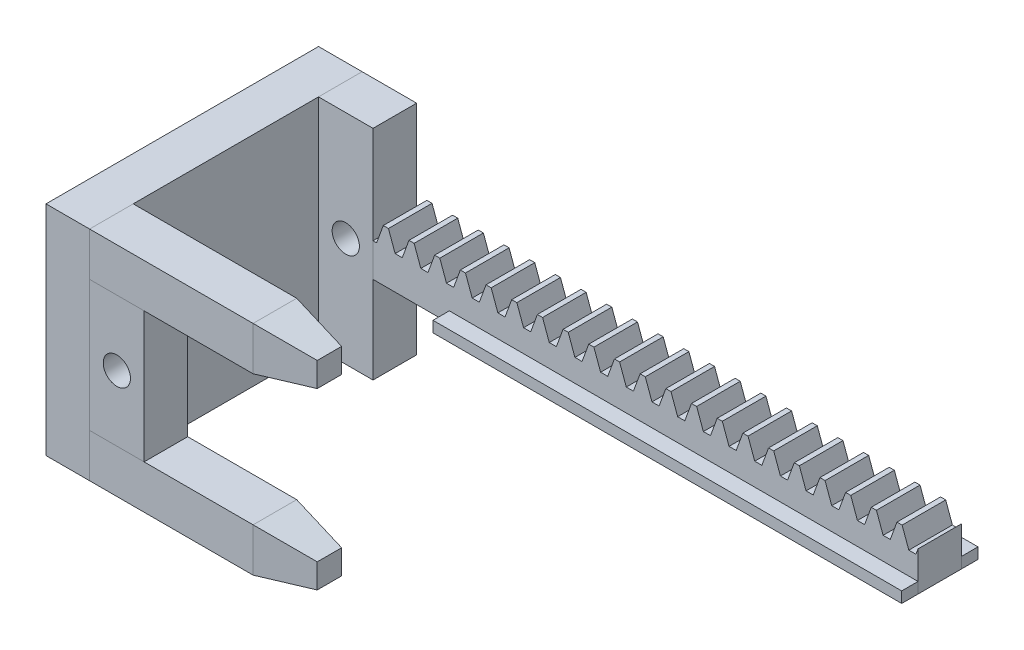
SolidWorks part; units mm, degrees
other "CutExtrude1"
other "BodyMoveCopy12"
other "BodyMoveCopy11"
other "BodyMoveCopy13"
other "CutExtrude41"
other "CutExtrude42"
other "BodyMoveCopy15"
other "Body-MoveCopy14"
other "CutExtrude2" parameters "D1"=40, "Dr"=15.875, "MPH"=8, "Hub_dia"=25.4, "Diameter"=38.1, "Num_teeth"=7, "D2"=101.9804, "Pitch_radius"=46.4154, "Pitch"=0.6667, "Width"=8.636, "Chamfer_wid"=3.175, "Chamfer_dep"=12.7, "Overall_len"=25.4, "Show_teeth"=998, "Thickness"=12.7, "OAL"=25.4001, "T_dim"=21.59, "Ap"=20, "H"=19.05, "Pitch_height"=8, "F"=44.45, "Backlash"=0.053, "Addendum_factor"=25.3187, "Dedendum_factor"=11.9164, "Fillet_factor"=5.08, "Addendum_fac"=1, "Dedendum_fac"=1.25, "Clearance_fac"=0.25, "Dedendum_add"=0.001, "Length"=100, "Module"=1.5, "Blank_height"=9.5, "Face_width"=8
extrude "Blank" add sketch "BlankSke" against normal blind 8
sketch "BlankSke" plane through (0, 0, 0) normal (0, 0, 1) x (1, 0, 0)
  line L1 (0, 0) -> (100, 0)
  line L2 (0, 0) -> (0, 9.5)
  line L3 (0, 9.5) -> (100, 9.5)
  line L4 (100, 0) -> (100, 9.5)
  dimension "Length" = 100
ref_plane "Plane1" through (0, 0, 0) normal (0, 0, 1) x (1, 0, 0)
ref_plane "Plane2" through (0, 0, 0) normal (0, 1, 0) x (1, 0, 0)
ref_plane "Plane3" through (0, 0, 0) normal (1, 0, 0) x (0, 0, -1)
sketch "HoldingSke" plane through (0, 0, 0) normal (0, 1, 0) x (1, 0, 0)
  line L0 (0, 0) -> (0.0928, 0.6602)
  line L1 (-15, 0) -> (100, 0) construction
  line L2 (0, 0) -> (-2.1039, 2.3779)
  line L3 (0, 0) -> (-11.863, 4.5341)
  line L4 (0, 0) -> (7.9495, 3.3743)
  line L5 (0, 0) -> (-23.7986, -8.8762)
  line L6 (0, 0) -> (-10.5278, -7.1032)
  line L9 (-71.009, 38.7566) -> (22.9603, 72.9586)
  line L10 (-76.2, 3.8779) -> (-68.2, 3.8779)
  line L11 (0, 0) -> (-8, 0)
  line L12 (-76.2, 101.6) -> (-76.147, 101.6)
  line L13 (24.9733, 27.94) -> (52.9518, 28.4284)
  line L14 (24.9733, 27.94) -> (24.9743, 27.94)
  line L15 (24.9733, 27.94) -> (100.4006, 29.5858)
  circle A0 centre (0, 0) radius 19.05
  circle A1 centre (0, 0) radius 4
  circle A2 centre (0, 0) radius 12.7
  dimension "Num_teeth" = 23
  dimension "Width" = 8
  dimension "Length" = 100
  dimension "Pitch_height" = 8
sketch "TooCutSkeIll" plane through (0, 0, 0) normal (0, 0, 1) x (1, 0, 0)
  line L0 (-1.8687, 9.4605) -> (-0.7447, 6.3724)
  line L1 (-0.3914, 6.125) -> (0.3914, 6.125)
  line L2 (0.7447, 6.3724) -> (1.8687, 9.4605)
  line L3 (100, 9.5) -> (0, 9.5) construction
  line L4 (0, 0) -> (0, 64.897) construction
  line L5 (-13.208, 8) -> (12.954, 8) construction
  line L6 (0, 0) -> (100, 0) construction
  line L7 (1.3371, 8) -> (1.3371, 48.7463) construction
  line L8 (-1.3371, 8) -> (-1.3371, 48.7463) construction
  line L9 (1.9251, 9.5) -> (1.9251, 9.5254)
  line L10 (-1.9251, 9.5) -> (-1.9251, 9.5254)
  line L11 (-1.9251, 9.5254) -> (1.9251, 9.5254)
  arc A0 (0.3914, 6.125) -> (0.7447, 6.3724) centre (0.3914, 6.501) ccw
  arc A1 (-0.7447, 6.3724) -> (-0.3914, 6.125) centre (-0.3914, 6.501) ccw
  arc A2 (1.9251, 9.5) -> (1.8687, 9.4605) centre (1.9251, 9.44) ccw
  arc A3 (-1.8687, 9.4605) -> (-1.9251, 9.5) centre (-1.9251, 9.44) ccw
  dimension "Addendum_plus" = 1.5254
  dimension "Pitch_height" = 8
  dimension "Pressure_angle" = 20
  dimension "Gap_width" = 2.6742
  dimension "Dedendum" = 1.875
extrude "ToothCutIll" [suppressed] cut sketch "TooCutSkeIll" against normal through all
sketch "TooCutSkeSim" plane through (0, 0, 0) normal (0, 0, 1) x (1, 0, 0)
  line L0 (0.6547, 6.125) -> (-0.6547, 6.125)
  line L1 (1.8923, 9.5254) -> (0.6547, 6.125)
  line L2 (0, 17.4625) -> (0, 53.467) construction
  line L3 (1.8923, 9.5254) -> (-1.8923, 9.5254)
  line L6 (-1.8923, 9.5254) -> (-0.6547, 6.125)
  line L9 (-1.3371, 8) -> (1.3371, 8) construction
  line L10 (0, 0) -> (100, 0) construction
  line L11 (1.3371, 8) -> (1.3371, 53.467) construction
  line L12 (-1.3371, 8) -> (-1.3371, 53.467) construction
  dimension "Addendum_plus" = 1.5254
  dimension "Pitch_height" = 8
  dimension "Pressure_angle" = 20
  dimension "Gap_width" = 2.6742
  dimension "Dedendum" = 1.875
extrude "ToothCutSim" cut sketch "TooCutSkeSim" against normal through all
pattern_linear "TeethCuts" count 22 spacing 4.7124 along (1, 0, 0) of "ToothCutIll", "ToothCutSim"
sketch "Sketch1" plane through (0, 0, 0) normal (-1, 0, 0) x (0, 0, 1)
  line L0 (0, 0) -> (3, 0)
  line L1 (3, 0) -> (3, 2)
  line L2 (3, 2) -> (0, 2)
  line L3 (0, 6.125) -> (0, 0) construction
  line L4 (0, 2) -> (0, 0)
  dimension "D1" = 3
  dimension "D2" = 2
extrude "Boss-Extrude1" add sketch "Sketch1" against normal blind 100 separate body
ref_plane "Plane4" through (0, 0, -4) normal (0, 0, -1) x (-1, 0, 0)
sketch "Sketch2" plane through (0, 0, 0) normal (0, -1, 0) x (-1, 0, 0)
  line L0 (0, 0) -> (-100, 0) construction
  line L1 (0, 8) -> (0, 0) construction
  line L2 (-100, 8) -> (-100, 0) construction
  line L3 (-100, -3) -> (0, -3) construction
  dimension "D1" = 3
sketch "Sketch4" plane through (0, 0, 0) normal (-1, 0, 0) x (0, 0, 1)
  line L0 (-8, -16) -> (-8, 24)
  line L1 (-8, 24) -> (42, 24)
  line L2 (42, 24) -> (42, -16)
  line L3 (42, -16) -> (-8, -16)
  line L4 (-8, 0) -> (0, 0) construction
  line L5 (0, 6.125) -> (0, 0) construction
  dimension "D1" = 40
  dimension "D2" = 50
  dimension "D3" = 24
  dimension "D4" = 42
extrude "Boss-Extrude2" add sketch "Sketch4" along normal blind 8 separate body
sketch "Sketch5" plane through (0, 0, 0) normal (1, 0, 0) x (0, 0, -1)
  line L0 (-42, 24) -> (-34, 24)
  line L1 (-42, 24) -> (8, 24) construction
  line L2 (-34, 24) -> (-34, 16)
  line L3 (-34, 16) -> (-42, 16)
  line L4 (-42, -16) -> (-42, 24) construction
  line L5 (-42, 16) -> (-42, 24)
  dimension "D1" = 8
  dimension "D2" = 8
extrude "Boss-Extrude3" add sketch "Sketch5" along normal blind 30 separate body
ref_plane "Plane5" through (0, 4, 0) normal (0, 1, 0) x (1, 0, 0)
sketch "Sketch6" plane through (30, 0, 0) normal (1, 0, 0) x (0, 0, -1)
  line L0 (-42, 16) -> (-42, 24)
  line L1 (-42, 24) -> (-34, 24)
  line L2 (-34, 24) -> (-42, 24) construction
  line L3 (-34, 16) -> (-34, 24) construction
  line L4 (-34, 24) -> (-34, 16)
  line L5 (-42, 16) -> (-34, 16) construction
  line L6 (-34, 16) -> (-42, 16)
  dimension "D1" = 8
extrude "Boss-Extrude4" add sketch "Sketch6" along normal blind 10 draft 10 separate body
sketch "Sketch8" plane through (0, 0, -8) normal (0, 0, -1) x (-1, 0, 0)
  line L0 (0, 24) -> (0, -16)
  line L1 (0, -16) -> (-10, -16)
  line L2 (-10, -16) -> (-10, 24)
  line L3 (-10, 24) -> (0, 24)
  line L4 (8, 24) -> (8, -16) construction
  line L6 (8, -16) -> (0, -16) construction
  dimension "D1" = 10
  dimension "D2" = 40
  dimension "D3" = 18
  dimension "D4" = 40
extrude "Boss-Extrude5" add sketch "Sketch8" against normal blind 8 separate body
sketch "Sketch9" plane through (0, 2, 0) normal (0, 1, 0) x (1, 0, 0)
  line L1 (0, -3) -> (14, -3)
  line L2 (0, -3) -> (0, 0)
  line L3 (0, 0) -> (14, 0)
  line L4 (14, -3) -> (14, 0)
  dimension "D1" = 14
  dimension "D2" = 3
  dimension "D3" = 100
  dimension "D4" = 3
extrude "Cut-Extrude1" cut sketch "Sketch9" against normal up to next (2 mm away)
sketch "Sketch10" plane through (10, 0, 0) normal (1, 0, 0) x (0, 0, -1)
  line L0 (8, 0) -> (11, 0)
  line L1 (11, 0) -> (11, 2)
  line L2 (11, 2) -> (8, 2)
  line L3 (8, 0) -> (8, 7.1833) construction
  line L4 (8, 2) -> (8, 0)
  dimension "D1" = 3
  dimension "D2" = 2
extrude "Boss-Extrude6" add sketch "Sketch10" along normal blind 90 separate body
sketch "Sketch11" plane through (0, 2, 0) normal (0, 1, 0) x (1, 0, 0)
  line L0 (10, 8) -> (10, 11)
  line L1 (10, 11) -> (14, 11)
  line L2 (100, 11) -> (10, 11) construction
  line L3 (14, 11) -> (14, 8)
  line L4 (13.4825, 8) -> (14.7918, 8) construction
  line L5 (14, 8) -> (10, 8)
  dimension "D1" = 4
extrude "Cut-Extrude2" cut sketch "Sketch11" against normal blind 90
sketch "Sketch12" plane through (0, 0, 0) normal (1, 0, 0) x (0, 0, -1)
  line L1 (-42, -16) -> (-34, -16)
  line L2 (-42, -16) -> (-42, -8)
  line L3 (-42, -8) -> (-34, -8)
  line L4 (-34, -16) -> (-34, -8)
  dimension "D1" = 8
  dimension "D2" = 8
extrude "Boss-Extrude7" add sketch "Sketch12" along normal blind 30 separate body
sketch "Sketch13" plane through (30, 0, 0) normal (1, 0, 0) x (0, 0, -1)
  line L1 (-42, -16) -> (-34, -16)
  line L2 (-42, -16) -> (-42, -8)
  line L3 (-42, -8) -> (-34, -8)
  line L4 (-34, -16) -> (-34, -8)
extrude "Boss-Extrude8" add sketch "Sketch13" along normal blind 10 draft 10 separate body
sketch "Sketch14" plane through (0, 0, 42) normal (0, 0, 1) x (1, 0, 0)
  line L0 (30, 16) -> (0, 16) construction
  line L1 (0, -8) -> (10, -8)
  line L2 (0, -8) -> (0, 16)
  line L3 (0, 16) -> (10, 16)
  line L4 (10, -8) -> (10, 16)
  dimension "D1" = 10
extrude "Boss-Extrude9" add sketch "Sketch14" against normal blind 8 separate body
sketch "Sketch15" plane through (0, 0, 42) normal (0, 0, 1) x (1, 0, 0)
  line L0 (0, -16) -> (0, 24) construction
  line L1 (30, 16) -> (0, 16) construction
  circle A0 centre (5, 4) radius 2.5
  dimension "D1" = 5
  dimension "D2" = 5
  dimension "D3" = 12
move or copy body "Body-Move/Copy1" bodies to move or copy 106 105 108 155 156 111 157 copy no translate (-10, 0, 0)
sketch "Sketch16" plane through (0, 0, 42) normal (0, 0, 1) x (1, 0, 0)
  line L0 (20, 16) -> (-10, 16) construction
  line L1 (-10, -16) -> (-10, 24) construction
  circle A0 centre (-5, 4) radius 2.5
  dimension "D1" = 5
  dimension "D2" = 12
  dimension "D3" = 5
extrude "Cut-Extrude4" cut sketch "Sketch16" against normal through all
equation "' \"Module@HoldingSke\" = 6.35"
equation "' \"Num_teeth@HoldingSke\" = 12"
equation "' \"Ap@HoldingSke\" =  20"
equation "' \"Ap@HoldingSke\" = 20"
equation "' \"Width@HoldingSke\" = 0.25 * 25.4"
equation "' \"Show_teeth@HoldingSke\" = 500"
equation "' \"Backlash@HoldingSke\" = 0.009 * 25.4"
equation "' \"Addendum_fac@HoldingSke\" = 1.0"
equation "' \"Dedendum_fac@HoldingSke\" = 1.25"
equation "' \"Dedendum_add@HoldingSke\" = 0.00005 * 25.4"
equation "' \"Clearance_fac@HoldingSke\" = 0.25"
equation "' \"Pitch_height@HoldingSke\" = 1 * 25.4"
equation "' \"Length@HoldingSke\" = 4.71 * 25.4"
equation "\"Pitch@HoldingSke\" = 1 / \"Module@HoldingSke\""
equation "\"MPH@HoldingSke\" = \"Dedendum_fac@HoldingSke\" / \"Pitch@HoldingSke\" + 2 * \"Dedendum_add@HoldingSke\" + 0.002 * 25.4"
equation "\"MPH@HoldingSke\" = ((sgn( \"MPH@HoldingSke\" - \"Pitch_height@HoldingSke\")+1)*( \"MPH@HoldingSke\" - \"Pitch_height@HoldingSke\"))/2 + \"Pitch_height@HoldingSke\""
equation "\"Blank_height@BlankSke\" = \"Pitch_height@HoldingSke\" + \"Addendum_fac@HoldingSke\"  / \"Pitch@HoldingSke\" "
equation "\"Length@BlankSke\" =  \"Length@HoldingSke\""
equation "\"Face_width@Blank\" = \"Width@HoldingSke\""
equation "\"Pressure_angle@TooCutSkeIll\" = \"Ap@HoldingSke\""
equation "\"Addendum_plus@TooCutSkeIll\" =  \"Addendum_fac@HoldingSke\"  / \"Pitch@HoldingSke\" + 0.001 *25.4"
equation "\"Dedendum@TooCutSkeIll\" = \"Dedendum_fac@HoldingSke\"  / \"Pitch@HoldingSke\""
equation "\"Pitch_height@TooCutSkeIll\" =  \"MPH@HoldingSke\""
equation "\"Gap_width@TooCutSkeIll\" = 3.14159265 / 2 / \"Pitch@HoldingSke\" + 6 * \"Backlash@HoldingSke\""
equation "\"Pressure_angle@TooCutSkeSim\" = \"Ap@HoldingSke\""
equation "\"Addendum_plus@TooCutSkeSim\" =  \"Addendum_fac@HoldingSke\"  / \"Pitch@HoldingSke\" + 0.001 * 25.4"
equation "\"Dedendum@TooCutSkeSim\" = \"Dedendum_fac@HoldingSke\"  / \"Pitch@HoldingSke\""
equation "\"Pitch_height@TooCutSkeSim\" =  \"MPH@HoldingSke\""
equation "\"Gap_width@TooCutSkeSim\" = 3.14159265 / 2 / \"Pitch@HoldingSke\" + 6 * \"Backlash@HoldingSke\""
equation "\"Root_fillet@TooCutSkeIll\" = \"Clearance_fac@HoldingSke\" / \"Pitch@HoldingSke\" + \"Dedendum_add@HoldingSke\""
equation "\"Break_rad@TooCutSkeIll\" = 0.02 / \"Pitch@HoldingSke\" * 2"
equation "\"Linear_pitch@TeethCuts\" = 3.14159265 / \"Pitch@HoldingSke\""
equation "\"Num_teeth@HoldingSke\" = int( ( \"Length@HoldingSke\" + 0 ) / (3.14159265 / \"Pitch@HoldingSke\")) + 0.9999  + 1"
equation " \"Num_teeth@TeethCuts\" = int( \"Show_teeth@HoldingSke\" ) + 1"
equation " \"Num_teeth@TeethCuts\" = ((sgn( \"Num_teeth@TeethCuts\" - \"Num_teeth@HoldingSke\" )-1)*( \"Num_teeth@TeethCuts\" - \"Num_teeth@HoldingSke\" ))/-2+ \"Num_teeth@HoldingSke\""
equation " \"Num_teeth@TeethCuts\" = ((sgn( \"Num_teeth@TeethCuts\" - 2.0)+1)*( \"Num_teeth@TeethCuts\" - 2.0))/2 +2.0"
